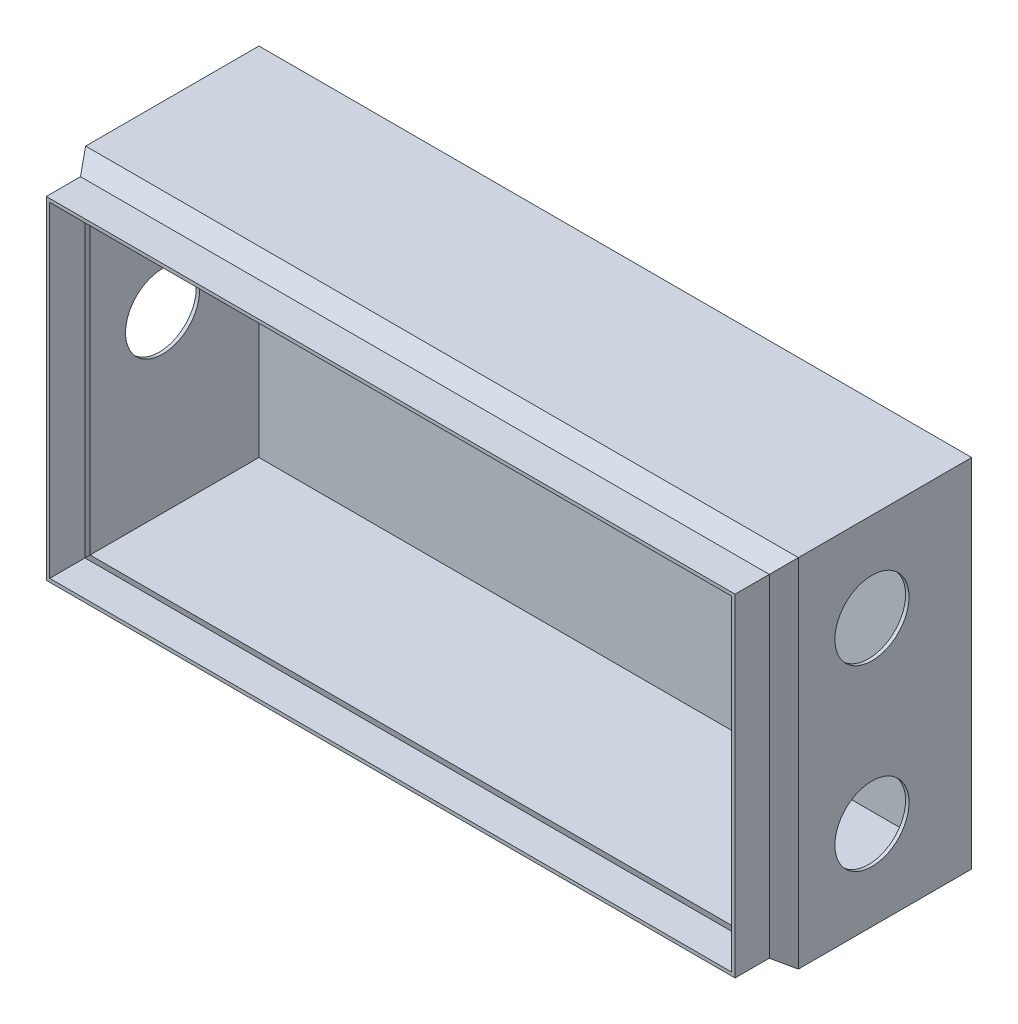
SolidWorks part; units mm, degrees
ref_plane "前视基准面" through (0, 0, 0) normal (0, 0, 1) x (1, 0, 0)
ref_plane "上视基准面" through (0, 0, 0) normal (0, 1, 0) x (1, 0, 0)
ref_plane "右视基准面" through (0, 0, 0) normal (1, 0, 0) x (0, 0, -1)
sketch "草图1" plane through (0, 0, 0) normal (0, 0, 1) x (1, 0, 0)
  line L0 (-125, -62.5) -> (-125, 62.5)
  line L1 (-125, -62.5) -> (125, -62.5)
  line L2 (-125, 62.5) -> (125, 62.5)
  line L3 (125, -62.5) -> (125, 62.5)
  line L4 (-125, -62.5) -> (125, 62.5) construction
  line L5 (-125, 62.5) -> (125, -62.5) construction
  point P1 (0, 0)
  dimension "D1" = 250
  dimension "D2" = 125
extrude "凸台-拉伸1" add sketch "草图1" along normal blind 60.8
sketch "草图4" plane through (0, 0, 60.8) normal (0, 0, 1) x (1, 0, 0)
  line L0 (125, -62.5) -> (125, 62.5) construction
  line L1 (-125, -62.5) -> (125, -62.5) construction
  line L2 (-125, 62.5) -> (-125, -62.5) construction
  line L3 (125, 62.5) -> (-125, 62.5) construction
  line L4 (125, -62.5) -> (125, 62.5)
  line L5 (-125, -62.5) -> (125, -62.5)
  line L6 (-125, 62.5) -> (-125, -62.5)
  line L7 (125, 62.5) -> (-125, 62.5)
extrude "凸台-拉伸2" add sketch "草图4" along normal blind 6 draft 35
sketch "草图5" plane through (0, 0, 66.8) normal (0, 0, 1) x (1, 0, 0)
  line L0 (120.7988, -58.2988) -> (120.7988, 58.2988) construction
  line L1 (-120.7988, -58.2988) -> (120.7988, -58.2988) construction
  line L2 (-120.7988, 58.2988) -> (-120.7988, -58.2988) construction
  line L3 (120.7988, 58.2988) -> (-120.7988, 58.2988) construction
  line L4 (120.7988, -58.2988) -> (120.7988, 58.2988)
  line L5 (-120.7988, -58.2988) -> (120.7988, -58.2988)
  line L6 (-120.7988, 58.2988) -> (-120.7988, -58.2988)
  line L7 (120.7988, 58.2988) -> (-120.7988, 58.2988)
extrude "凸台-拉伸3" add sketch "草图5" along normal blind 12
shell "抽壳1" thickness 1.2
sketch "草图6" plane through (0, 0, 0) normal (1, 0, 0) x (0, 0, -1)
  line L1 (-60.8, 0) -> (0, 0) construction
  line L2 (-35, -62.5) -> (-35, 62.5)
  line L3 (-35, -62.5) -> (-35, 62.5) construction
  line L4 (-60.8, -62.5) -> (-60.8, 62.5) construction
  circle A0 centre (-35, 0) radius 13
  circle A1 centre (-35, -31.25) radius 13
  circle A2 centre (-35, 31.25) radius 13
  dimension "D2" = 26
  dimension "D1" = 35
sketch "草图9" plane through (-125, 0, 0) normal (-1, 0, 0) x (0, 0, 1)
  circle A0 centre (35, 0) radius 13 construction
  circle A1 centre (35, 0) radius 13
extrude "切除-拉伸2" cut sketch "草图9" against normal blind 12
sketch "草图10" plane through (125, 0, 0) normal (1, 0, 0) x (0, 0, -1)
  circle A0 centre (-35, 31.25) radius 13 construction
  circle A1 centre (-35, -31.25) radius 13 construction
  circle A2 centre (-35, 31.25) radius 13
  circle A3 centre (-35, -31.25) radius 13
extrude "切除-拉伸3" cut sketch "草图10" against normal blind 12
